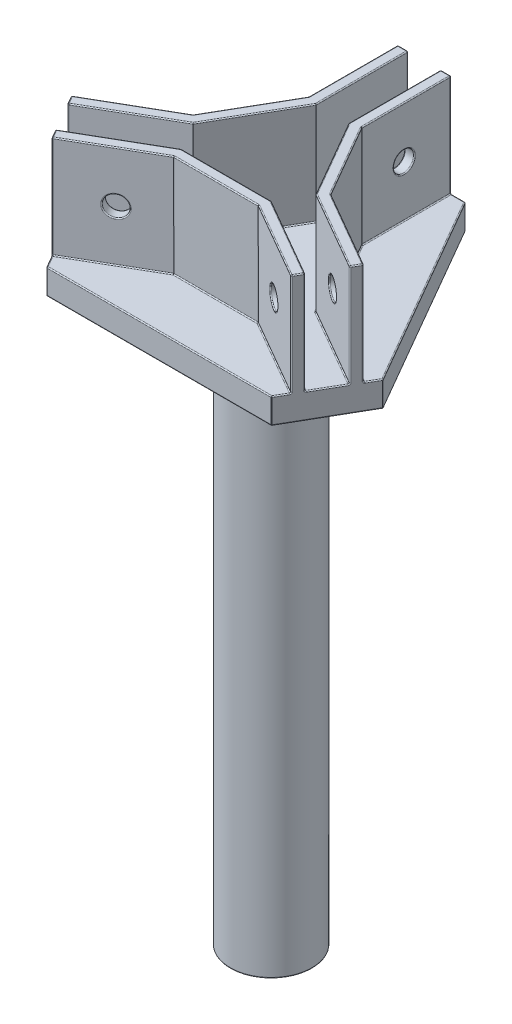
SolidWorks part; units mm, degrees
ref_plane "Front Plane" through (0, 0, 0) normal (0, 0, 1) x (1, 0, 0)
ref_plane "Top Plane" through (0, 0, 0) normal (0, 1, 0) x (1, 0, 0)
ref_plane "Right Plane" through (0, 0, 0) normal (1, 0, 0) x (0, 0, -1)
sketch "Sketch1" plane through (0, 0, 0) normal (0, 1, 0) x (1, 0, 0)
  line L0 (-13, -7.5056) -> (0, 0) construction
  line L1 (0, 0) -> (13, -7.5056) construction
  line L2 (13, -7.5056) -> (0, 0) construction
  line L3 (0, 0) -> (0, 15.0111) construction
  line L4 (-4, 15.0111) -> (4, 15.0111)
  line L5 (-15, -4.0415) -> (-11, -10.9697)
  line L6 (15, -4.0415) -> (11, -10.9697)
  line L7 (-15, -4.0415) -> (-4, 15.0111)
  line L8 (4, 15.0111) -> (15, -4.0415)
  line L9 (11, -10.9697) -> (-11, -10.9697)
  point P7 (0, 15.0111)
  point P10 (-13, -7.5056)
  point P14 (13, -7.5056)
  dimension "D1" = 120
  dimension "D2" = 120
  dimension "D3" = 8
  dimension "D4" = 22
extrude "Boss-Extrude1" add sketch "Sketch1" against normal blind 2.5
sketch "Sketch2" plane through (0, 0, 0) normal (0, 1, 0) x (1, 0, 0)
  line L0 (-13, -7.5056) -> (0, 0) construction
  line L1 (-15, -4.0415) -> (-11, -10.9697) construction
  line L2 (0, 0) -> (13, -7.5056) construction
  line L3 (11, -10.9697) -> (15, -4.0415) construction
  line L4 (0, 0) -> (0, 15.0111) construction
  line L5 (4, 15.0111) -> (-4, 15.0111) construction
  line L6 (-12.2, -8.8912) -> (-4.4058, -4.3912)
  line L7 (-4.4058, -4.3912) -> (4.4058, -4.3912)
  line L8 (4.4058, -4.3912) -> (12.2, -8.8912)
  line L9 (-11.7, -9.7572) -> (-4.1378, -5.3912)
  line L10 (-4.1378, -5.3912) -> (4.1378, -5.3912)
  line L11 (4.1378, -5.3912) -> (11.7, -9.7572)
  line L12 (-12.2, -8.8912) -> (-11.7, -9.7572)
  line L13 (12.2, -8.8912) -> (11.7, -9.7572)
  line L14 (-1.6, 15.0111) -> (-2.6, 15.0111)
  line L15 (-1.6, 15.0111) -> (-1.6, 6.0111)
  line L16 (-2.6, 15.0111) -> (-2.6, 6.2791)
  line L17 (-1.6, 6.0111) -> (-6.0058, -1.6199)
  line L18 (-2.6, 6.2791) -> (-6.7378, -0.8879)
  line L19 (-6.0058, -1.6199) -> (-13.8, -6.1199)
  line L20 (-6.7378, -0.8879) -> (-14.3, -5.2539)
  line L21 (-13.8, -6.1199) -> (-14.3, -5.2539)
  line L22 (13.8, -6.1199) -> (14.3, -5.2539)
  line L23 (13.8, -6.1199) -> (6.0058, -1.6199)
  line L24 (14.3, -5.2539) -> (6.7378, -0.8879)
  line L25 (6.0058, -1.6199) -> (1.6, 6.0111)
  line L26 (6.7378, -0.8879) -> (2.6, 6.2791)
  line L27 (1.6, 6.0111) -> (1.6, 15.0111)
  line L28 (2.6, 6.2791) -> (2.6, 15.0111)
  line L29 (1.6, 15.0111) -> (2.6, 15.0111)
  circle A0 centre (0, 0) radius 4 construction
  point P14 (0, -4.3912)
  point P40 (0, 0)
  dimension "D1" = 8
  dimension "D2" = 9
  dimension "D3" = 9
  dimension "D4" = 1.6
  dimension "D5" = 1
  dimension "D6" = 3
extrude "Boss-Extrude2" add sketch "Sketch2" along normal blind 10
sketch "Sketch3" plane through (0, -2.5, 0) normal (0, -1, 0) x (1, 0, 0)
  circle A0 centre (0, 0) radius 4 construction
  circle A1 centre (0, 0) radius 4
extrude "Boss-Extrude3" add sketch "Sketch3" along normal blind 55
sketch "Sketch5" plane through (-1.3, 0, 2.2517) normal (-0.5, 0, 0.866) x (0.866, 0, 0.5)
  line L0 (15.0111, 5) -> (6.2791, 5) construction
  line L1 (15.0111, 10) -> (15.0111, 0) construction
  line L2 (6.2791, 10) -> (6.2791, 0) construction
  circle A0 centre (10.427, 5) radius 1
  dimension "D1" = 2
extrude "Cut-Extrude1" cut sketch "Sketch5" against normal through all
pattern_circular "CirPattern1" count 3 over 360 about axis through (0, -57.5, 0) along (0, 1, 0) of "Cut-Extrude1"
fillet "Fillet1" radius 0.1 104 edges at (2.6, 5, -11.427) (-11.1961, 5, 3.4618) (1.6, 5, -11.427) (-2.6, 5, -11.427) (-1.6, 5, -9.427) (-10.6961, 5, 4.3279) (-7.364, 5, 6.0991) (-8.5961, 5, 7.9652) (8.5961, 5, 7.9652) (11.1961, 5, 3.4618) (8.964, 5, 3.3279) (9.0961, 5, 7.0991) (0, -2.5, -4) (13.8, 5, 6.1199) (14.3, 5, 5.2539) (6.7378, 5, 0.8879) (2.6, 5, -6.2791) (2.6, 5, -15.0111) (1.6, 5, -15.0111) (1.6, 5, -6.0111) (6.0058, 5, 1.6199) (3.8029, 10, -2.1956) (1.6, 10, -10.5111) (2.1, 10, -15.0111) (2.6, 10, -10.6451) (4.6689, 10, -2.6956) (10.5189, 10, 3.0709) (14.05, 10, 5.6869) (9.9029, 10, 3.8699) (3.8029, 0, -2.1956) (1.6, 0, -10.5111) (2.6, 0, -10.6451) (4.6689, 0, -2.6956) (10.5189, 0, 3.0709) (9.9029, 0, 3.8699) (-1.6, 5, -15.0111) (-2.6, 5, -15.0111) (-2.6, 5, -6.2791) (-6.7378, 5, 0.8879) (-14.3, 5, 5.2539) (-13.8, 5, 6.1199) (-6.0058, 5, 1.6199) (-1.6, 5, -6.0111) (-3.8029, 10, -2.1956) (-9.9029, 10, 3.8699) (-14.05, 10, 5.6869) (-10.5189, 10, 3.0709) (-4.6689, 10, -2.6956) (-2.6, 10, -10.6451) (-2.1, 10, -15.0111) (-1.6, 10, -10.5111) (-3.8029, 0, -2.1956) (-9.9029, 0, 3.8699) (-10.5189, 0, 3.0709) (-4.6689, 0, -2.6956) (-2.6, 0, -10.6451) (-1.6, 0, -10.5111) (-7.9189, 0, 7.5742) (0, 0, 5.3912) (7.9189, 0, 7.5742) (8.3029, 0, 6.6412) (0, 0, 4.3912) (-8.3029, 0, 6.6412) (-11.95, 10, 9.3242) (-7.9189, 10, 7.5742) (0, 10, 5.3912) (7.9189, 10, 7.5742) (11.95, 10, 9.3242) (8.3029, 10, 6.6412) (0, 10, 4.3912) (-8.3029, 10, 6.6412) (-12.2, 5, 8.8912) (-4.4058, 5, 4.3912) (4.4058, 5, 4.3912) (12.2, 5, 8.8912) (11.7, 5, 9.7572) (4.1378, 5, 5.3912) (-4.1378, 5, 5.3912) (-11.7, 5, 9.7572) (-9.5, 0, -5.4848) (-11.35, 0, 10.3634) (-13, 0, 7.5056) (-14.65, 0, 4.6477) (0, 0, 10.9697) (14.65, 0, 4.6477) (13, 0, 7.5056) (11.35, 0, 10.3634) (9.5, 0, -5.4848) (-3.3, 0, -15.0111) (0, 0, -15.0111) (3.3, 0, -15.0111) (-9.5, -2.5, -5.4848) (-13, -2.5, 7.5056) (0, -2.5, 10.9697) (13, -2.5, 7.5056) (9.5, -2.5, -5.4848) (0, -2.5, -15.0111) (-15, -1.25, 4.0415) (-11, -1.25, 10.9697) (11, -1.25, 10.9697) (15, -1.25, 4.0415) (4, -1.25, -15.0111) (-4, -1.25, -15.0111) (0, -57.5, -4)
